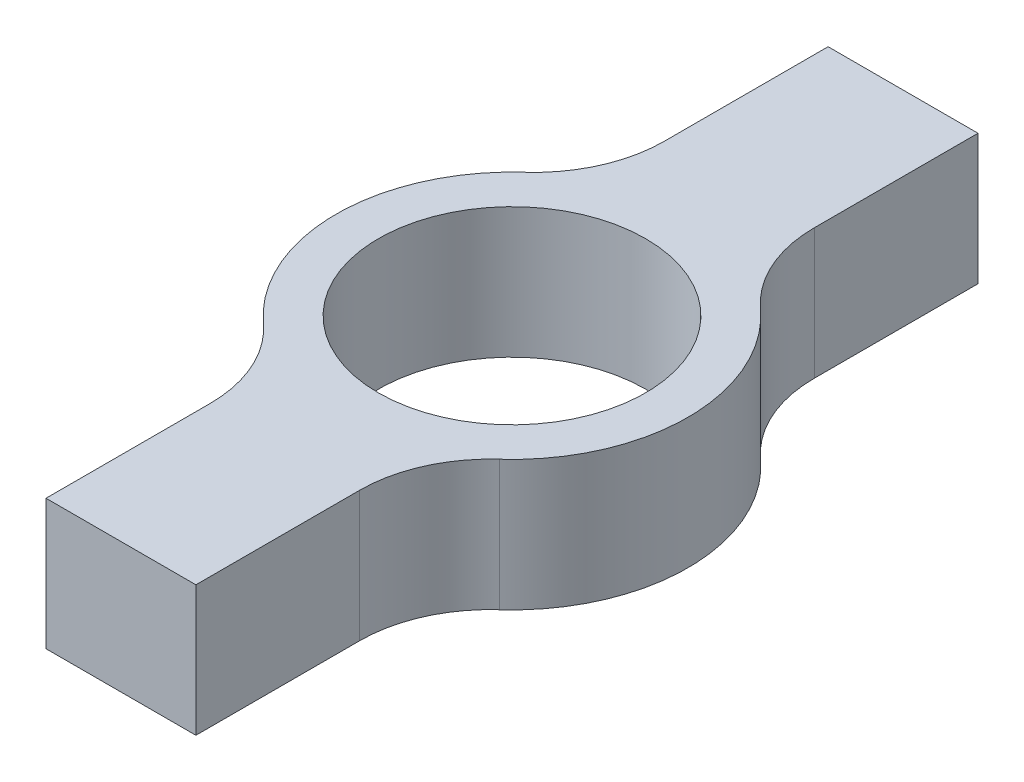
SolidWorks part; units mm, degrees
ref_plane "前视基准面" through (0, 0, 0) normal (0, 0, 1) x (1, 0, 0)
ref_plane "上视基准面" through (0, 0, 0) normal (0, 1, 0) x (1, 0, 0)
ref_plane "右视基准面" through (0, 0, 0) normal (1, 0, 0) x (0, 0, -1)
other "Configuration Table"
sketch "草图1" plane through (0, 0, 0) normal (0, 1, 0) x (1, 0, 0)
  circle A0 centre (0, 0) radius 13.5
  dimension "D1" = 27
extrude "凸台-拉伸1" add sketch "草图1" along normal blind 10
sketch "草图2" plane through (0, 10, 0) normal (0, 1, 0) x (1, 0, 0)
  line L0 (0, 0) -> (0, 13.5) construction
  line L1 (0, 0) -> (0, -13.5) construction
  line L3 (-5.75, 30) -> (5.75, 30)
  line L4 (-5.75, 30) -> (-5.75, -30)
  line L5 (-5.75, -30) -> (5.75, -30)
  line L6 (5.75, 30) -> (5.75, -30)
  circle A0 centre (0, 0) radius 13.5 construction
  dimension "D1" = 11.5
  dimension "D2" = 5.75
  dimension "D3" = 60
  dimension "D4" = 30
extrude "凸台-拉伸2" add sketch "草图2" against normal blind 10
sketch "草图3" plane through (0, 10, 0) normal (0, 1, 0) x (1, 0, 0)
  circle A0 centre (0, 0) radius 10.25
  dimension "D1" = 20.5
extrude "切除-拉伸1" cut sketch "草图3" against normal blind 10
fillet "圆角1" radius 10 4 edges at (5.75, 5, 12.2142) (5.75, 5, -12.2142) (-5.75, 5, -12.2142) (-5.75, 5, 12.2142)
